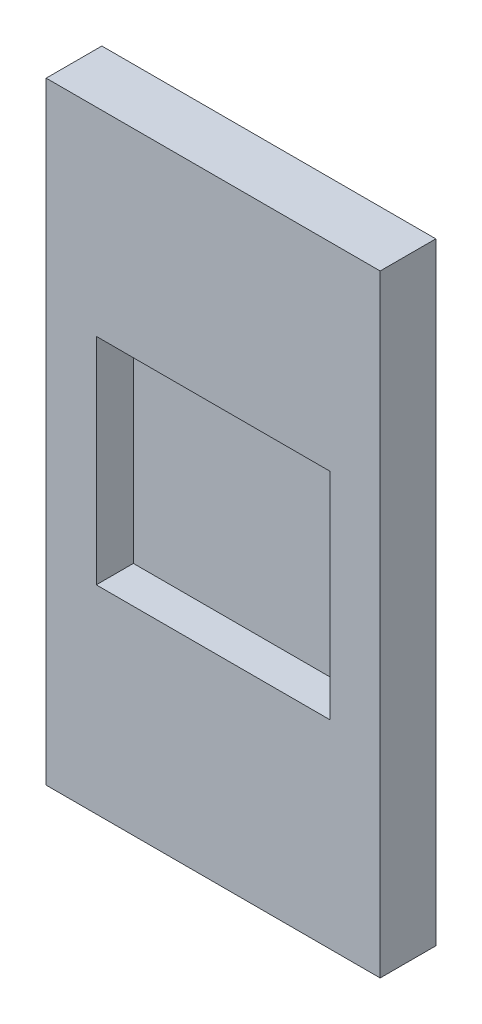
SolidWorks part; units mm, degrees
ref_plane "정면" through (0, 0, 0) normal (0, 0, 1) x (1, 0, 0)
ref_plane "윗면" through (0, 0, 0) normal (0, 1, 0) x (1, 0, 0)
ref_plane "우측면" through (0, 0, 0) normal (1, 0, 0) x (0, 0, -1)
sketch "스케치1" plane through (0, 0, 0) normal (0, 0, 1) x (1, 0, 0)
  line L1 (-9, -16.5) -> (9, -16.5)
  line L2 (-9, -16.5) -> (-9, 16.5)
  line L3 (-9, 16.5) -> (9, 16.5)
  line L4 (9, -16.5) -> (9, 16.5)
  line L5 (-9, -16.5) -> (9, 16.5) construction
  line L6 (-9, 16.5) -> (9, -16.5) construction
  point P0 (0, 0)
  dimension "D1" = 18
  dimension "D2" = 33
extrude "보스-돌출1" add sketch "스케치1" along normal blind 3
sketch "스케치2" plane through (0, 0, 3) normal (0, 0, 1) x (1, 0, 0)
  line L1 (-6.3, -5.8) -> (6.3, -5.8)
  line L2 (-6.3, -5.8) -> (-6.3, 5.8)
  line L3 (-6.3, 5.8) -> (6.3, 5.8)
  line L4 (6.3, -5.8) -> (6.3, 5.8)
  line L5 (-6.3, -5.8) -> (6.3, 5.8) construction
  line L6 (-6.3, 5.8) -> (6.3, -5.8) construction
  point P1 (0, 0)
  dimension "D1" = 12.6
  dimension "D2" = 11.6
extrude "컷-돌출1" cut sketch "스케치2" against normal blind 2
